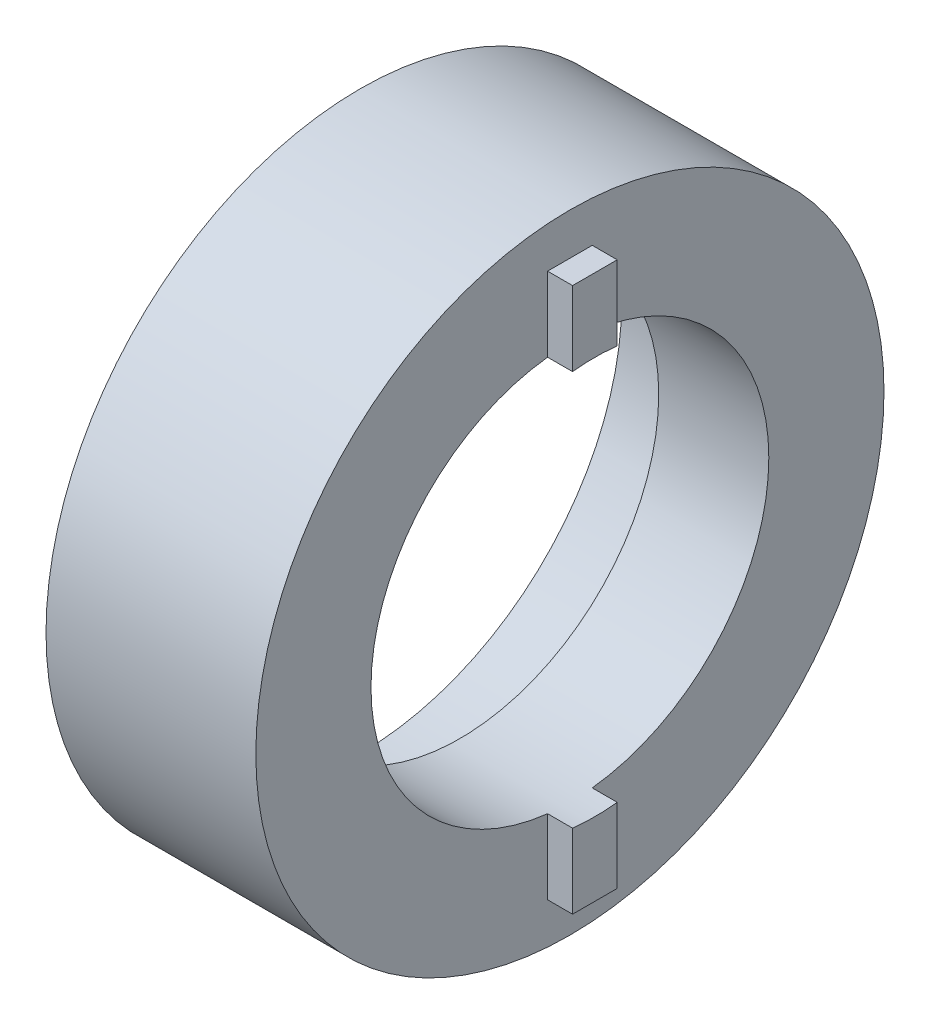
SolidWorks part; units mm, degrees
material "7075-T6 (SN)"
ref_plane "Front Plane" through (0, 0, 0) normal (0, 0, 1) x (1, 0, 0)
ref_plane "Top Plane" through (0, 0, 0) normal (0, 1, 0) x (1, 0, 0)
ref_plane "Right Plane" through (0, 0, 0) normal (1, 0, 0) x (0, 0, -1)
sketch "Sketch13" plane through (0, 0, 0) normal (1, 0, 0) x (0, 0, -1)
  circle A0 centre (0, 0) radius 30
  dimension "D1" = 60
extrude "Boss-Extrude11" add sketch "Sketch13" along normal blind 20.0406 separate body
sketch "Sketch14" plane through (0, 0, 0) normal (-1, 0, 0) x (0, 0, 1)
  circle A0 centre (0, 0) radius 25
  circle A1 centre (0, 0) radius 30 construction
  dimension "D1" = 50
extrude "Cut-Extrude2" cut sketch "Sketch14" against normal blind 9.525
sketch "Sketch16" plane through (20.0406, 0, 0) normal (1, 0, 0) x (0, 0, -1)
  line L1 (2.1336, 26) -> (-2.1336, 26)
  line L2 (2.1336, 26) -> (2.1336, -26)
  line L3 (2.1336, -26) -> (-2.1336, -26)
  line L4 (-2.1336, 26) -> (-2.1336, -26)
  line L5 (2.1336, 26) -> (-2.1336, -26) construction
  line L6 (2.1336, -26) -> (-2.1336, 26) construction
  point P0 (0, 0)
  dimension "D1" = 4.2672
  dimension "D2" = 52
extrude "Boss-Extrude12" add sketch "Sketch16" along normal blind 2.3876
sketch "Sketch15" plane through (0, 0, 0) normal (-1, 0, 0) x (0, 0, 1)
  circle A0 centre (0, 0) radius 19
  circle A1 centre (0, 0) radius 30 construction
  dimension "D1" = 38
extrude "Cut-Extrude3" cut sketch "Sketch15" against normal through all
